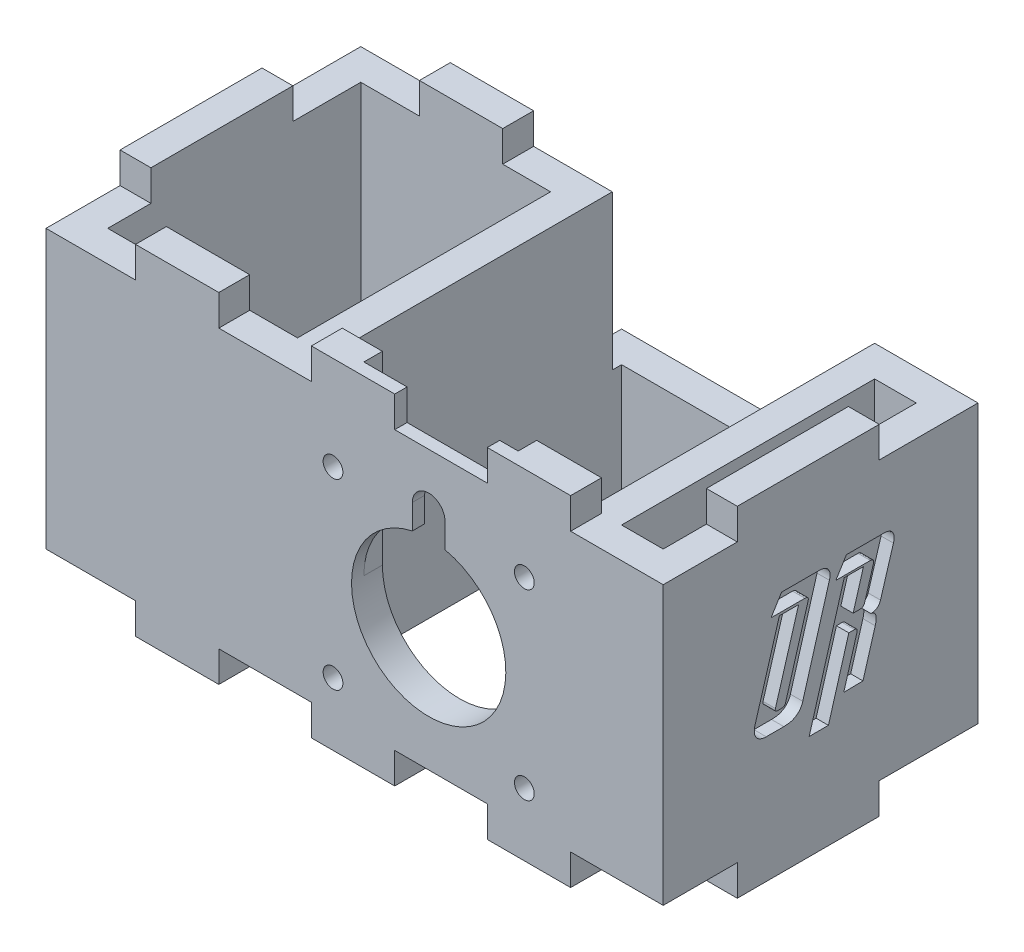
SolidWorks part; units mm, degrees
ref_plane "Plan de face" through (0, 0, 0) normal (0, 0, 1) x (1, 0, 0)
ref_plane "Plan de dessus" through (0, 0, 0) normal (0, 1, 0) x (1, 0, 0)
ref_plane "Plan de droite" through (0, 0, 0) normal (1, 0, 0) x (0, 0, -1)
sketch "Esquisse1" plane through (0, 0, 0) normal (0, 1, 0) x (1, 0, 0)
  line L1 (21.25, 23.75) -> (-21.25, 23.75)
  line L2 (21.25, 23.75) -> (21.25, -23.75)
  line L3 (21.25, -23.75) -> (-21.25, -23.75)
  line L4 (-21.25, 23.75) -> (-21.25, -23.75)
  line L5 (21.25, 23.75) -> (-21.25, -23.75) construction
  line L6 (21.25, -23.75) -> (-21.25, 23.75) construction
  point P0 (0, 0)
  dimension "D1" = 47.5
  dimension "D2" = 42.5
extrude "Extru.-Mince1" add sketch "Esquisse1" along normal blind 20 thin
sketch "Esquisse3" plane through (0, 0, 0) normal (0, -1, 0) x (1, 0, 0)
  line L0 (26.25, 28.75) -> (38, 28.75)
  line L1 (38, 28.75) -> (38, -22.25)
  line L3 (38, -22.25) -> (21.25, -22.25)
  line L4 (21.25, 23.75) -> (21.25, -23.75) construction
  line L5 (26.25, 28.75) -> (0, 28.75)
  line L6 (0, 28.75) -> (-26.25, 28.75)
  line L7 (-26.25, 28.75) -> (-62, 28.75)
  line L8 (-62, 28.75) -> (-62, -22.25)
  line L9 (-62, -22.25) -> (-21.25, -22.25)
  line L10 (-26.25, -28.75) -> (-26.25, 28.75) construction
  line L11 (33, 23.75) -> (33, -17.25)
  line L12 (33, -17.25) -> (26.25, -17.25)
  line L13 (26.25, 28.75) -> (26.25, -28.75) construction
  line L14 (26.25, -17.25) -> (26.25, 23.75)
  line L15 (26.25, 23.75) -> (33, 23.75)
  line L16 (-57, -17.25) -> (-26.25, -17.25)
  line L17 (-21.25, -23.75) -> (-21.25, 23.75) construction
  line L18 (-57, -17.25) -> (-57, 23.75)
  line L19 (-57, 23.75) -> (-26.25, 23.75)
  line L20 (-21.25, 23.75) -> (21.25, 23.75)
  line L21 (21.25, 23.75) -> (21.25, -22.25)
  line L22 (-21.25, 23.75) -> (-21.25, -22.25)
  line L23 (-26.25, 23.75) -> (-26.25, -17.25)
  line L24 (-26.25, 28.75) -> (26.25, 28.75) construction
  point P6 (26.25, 28.75)
  point P7 (-26.25, 28.75)
  dimension "D1" = 51
  dimension "D2" = 38
  dimension "D3" = 62
  dimension "D4" = 5
  dimension "D5" = 5
  dimension "D6" = 5
  dimension "D7" = 5
  dimension "D8" = 5
  dimension "D9" = 5
extrude "Boss.-Extru.1" add sketch "Esquisse3" against normal blind 45
sketch "Esquisse6" plane through (0, 45, 0) normal (0, 1, 0) x (1, 0, 0)
  line L0 (38, 6.25) -> (33, 6.25)
  line L1 (38, 22.25) -> (38, -28.75) construction
  line L2 (33, 17.25) -> (33, -23.75) construction
  line L3 (33, 6.25) -> (33, -16.75)
  line L4 (33, -16.75) -> (38, -16.75)
  line L5 (38, -16.75) -> (38, 6.25)
  line L6 (23, -28.75) -> (23, -23.75)
  line L7 (38, -28.75) -> (-62, -28.75) construction
  line L8 (33, -23.75) -> (26.25, -23.75) construction
  line L9 (23, -23.75) -> (9.5, -23.75)
  line L10 (-21.25, -23.75) -> (21.25, -23.75) construction
  line L11 (9.5, -23.75) -> (9.5, -28.75)
  line L12 (9.5, -28.75) -> (23, -28.75)
  line L13 (-5.5, -28.75) -> (-5.5, -23.75)
  line L14 (-5.5, -23.75) -> (-19, -23.75)
  line L15 (-19, -23.75) -> (-19, -28.75)
  line L16 (-19, -28.75) -> (-5.5, -28.75)
  line L17 (-34, -28.75) -> (-34, -23.75)
  line L18 (-34, -23.75) -> (-47.5, -23.75)
  line L19 (-47.5, -23.75) -> (-47.5, -28.75)
  line L20 (-47.5, -28.75) -> (-34, -28.75)
  line L23 (-47.5, 22.25) -> (-34, 22.25)
  line L24 (-47.5, 17.25) -> (-47.5, 22.25)
  line L25 (-34, 17.25) -> (-47.5, 17.25)
  line L26 (-34, 22.25) -> (-34, 17.25)
  line L28 (-62, -16.75) -> (-62, 6.25)
  line L29 (-57, -16.75) -> (-62, -16.75)
  line L30 (-57, 6.25) -> (-57, -16.75)
  line L31 (-62, 6.25) -> (-57, 6.25)
  point P6 (38, -5.25)
  point P15 (38, -5.25)
  dimension "D1" = 23
  dimension "D2" = 13.5
  dimension "D3" = 15
  dimension "D5" = 23.5
  dimension "D6" = 12
  dimension "D4" = 3
extrude "Boss.-Extru.3" add sketch "Esquisse6" along normal blind 5
sketch "Esquisse2" plane through (0, 0, 28.75) normal (0, 0, 1) x (1, 0, 0)
  line L0 (-62, 0) -> (38, 0) construction
  line L1 (0, -0.0585) -> (0, 20) construction
  line L2 (-15.5, 5.2) -> (15.5, 5.2) construction
  line L3 (38, 45) -> (38, 0) construction
  line L4 (0, 36.2159) -> (0, 28.8659) construction
  line L5 (2.65, 36.2159) -> (2.65, 32.2159)
  line L6 (-62, 0) -> (38, 0) construction
  line L7 (0, 20) -> (33.7261, 20) construction
  line L8 (-15.5, 34.8) -> (15.5, 34.8) construction
  line L9 (-2.65, 36.2159) -> (-2.65, 32.2159)
  arc A0 (-2.65, 32.2159) -> (2.65, 32.2159) centre (0, 20) ccw
  circle A1 centre (-15.5, 5.2) radius 1.6
  circle A2 centre (15.5, 5.2) radius 1.6
  circle A3 centre (15.5, 34.8) radius 1.6
  circle A4 centre (-15.5, 34.8) radius 1.6
  arc A5 (2.65, 36.2159) -> (-2.65, 36.2159) centre (0, 36.2159) ccw
  point P6 (0, -0.0585)
  point P10 (0, 5.2)
  point P20 (0, 34.8)
  point P21 (0, 40.0585)
  point P24 (0, 32.5)
  dimension "D2" = 25
  dimension "D3" = 3.2
  dimension "D4" = 3.2
  dimension "D8" = 2.65
  dimension "D1" = 20
  dimension "D5" = 5.2
  dimension "D6" = 31
  dimension "D7" = 38
  dimension "D9" = 7.35
  dimension "D10" = 5.3
  dimension "D11" = 4
extrude "Enlèv. mat.-Extru.1" cut sketch "Esquisse2" against normal up to next
sketch "Esquisse4" plane through (0, 0, 23.75) normal (0, 0, -1) x (-1, 0, 0)
  line L0 (-12.5, 20) -> (-12.5, 50)
  line L2 (-23, 50) -> (-9.5, 50) construction
  line L3 (12.5, 50) -> (12.5, 20)
  line L4 (-12.5, 50) -> (12.5, 50)
  circle A0 centre (0, 20) radius 12.5 construction
  arc A1 (-12.5, 20) -> (12.5, 20) centre (0, 20) cw
  dimension "D1" = 25
extrude "Enlèv. mat.-Extru.2" cut sketch "Esquisse4" against normal blind 3
ref_plane "Plan1" through (0, 22.5, 0) normal (0, -1, 0) x (-1, 0, 0)
mirror "Symétrie1" about plane through (0, 22.5, 0) normal (0, -1, 0) of "Boss.-Extru.3"
ref_plane "Plan2" through (0, 0, 0) normal (1, 0, 0) x (0, 0, -1)
sketch "Esquisse9" plane through (38, 0, 0) normal (1, 0, 0) x (0, 0, -1)
  line L0 (-15.0803, 15.3149) -> (8.5803, 15.3149) construction
  line L3 (-28.75, 45) -> (-28.75, 0) construction
  text T0 "OR" font "Avengeance Heroic Avenger" height in points 72
  point P2 (-3.25, 15.3149)
  dimension "D1" = 25.5
extrude "Enlèv. mat.-Extru.3" cut sketch "Esquisse9" against normal blind 2
